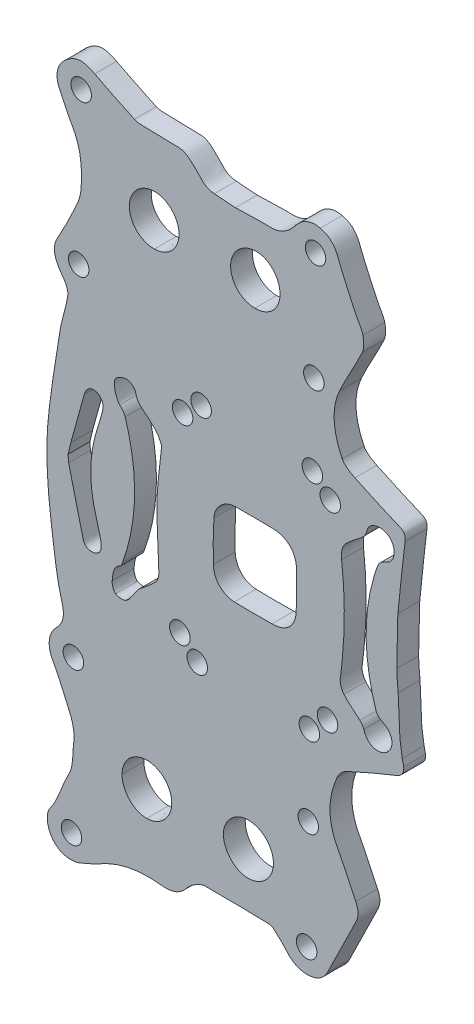
SolidWorks part; units mm, degrees
material "6063-T5"
ref_plane "Front Plane" through (0, 0, 0) normal (0, 0, 1) x (1, 0, 0)
ref_plane "Top Plane" through (0, 0, 0) normal (0, 1, 0) x (1, 0, 0)
ref_plane "Right Plane" through (0, 0, 0) normal (1, 0, 0) x (0, 0, -1)
sketch "Model" plane through (0, 0, 0) normal (0, 0, 1) x (1, 0, 0)
  spline S2 degree 3 poles (131.2621, -129.3744) (131.2709, -130.6129) (131.4296, -131.8502) (131.5219, -133.0884) knots 63 63 63 63 64 64 64 64
  spline S3 degree 3 poles (131.4744, -120.5521) (131.3543, -121.7786) (131.4323, -123.0237) (131.4013, -124.2598) (131.3586, -125.965) (131.2499, -127.67) (131.2621, -129.3744) knots 61 61 61 61 62 62 62 63 63 63 63
  spline S4 degree 3 poles (132.7951, -108.458) (132.2942, -112.482) (131.8696, -116.5161) (131.4744, -120.5521) knots 60 60 60 60 61 61 61 61
  spline S5 degree 3 poles (123.6028, -102.9962) (126.2109, -104.2579) (128.8702, -105.4196) (131.5464, -106.5318) (132.488, -106.9231) (132.9342, -107.3404) (132.7951, -108.458) knots 58 58 58 58 59 59 59 60 60 60 60
  spline S6 degree 3 poles (121.2866, -101.1379) (121.6823, -101.9488) (122.7224, -102.5703) (123.6028, -102.9962) knots 57 57 57 57 58 58 58 58
  spline S7 degree 3 poles (120.8083, -90.5998) (119.1912, -94.1412) (119.6269, -97.7367) (121.2866, -101.1379) knots 56 56 56 56 57 57 57 57
  spline S8 degree 3 poles (124.9527, -82.4768) (123.6758, -85.233) (122.0696, -87.8374) (120.8083, -90.5998) knots 55 55 55 55 56 56 56 56
  spline S9 degree 3 poles (125.0728, -79.6602) (125.2704, -80.5583) (125.3224, -81.6788) (124.9527, -82.4768) knots 54 54 54 54 55 55 55 55
  spline S10 degree 3 poles (117.2743, -66.6092) (119.1395, -67.0215) (120.0739, -68.2761) (120.7134, -70.0591) (121.5761, -72.4641) (122.7552, -74.7568) (123.8228, -77.0865) (124.2216, -77.9567) (124.8735, -78.7549) (125.0728, -79.6602) knots 51 51 51 51 52 52 52 53 53 53 54 54 54 54
  spline S11 degree 3 poles (112.7784, -68.4405) (113.9363, -66.9761) (115.3754, -66.1895) (117.2743, -66.6092) knots 50 50 50 50 51 51 51 51
  spline S12 degree 3 poles (101.7547, -71.1306) (103.8217, -71.1462) (105.895, -70.9292) (107.9557, -71.0251) (110.1482, -71.1272) (111.5494, -69.9949) (112.7784, -68.4405) knots 48 48 48 48 49 49 49 50 50 50 50
  spline S13 degree 3 poles (97.9186, -70.8362) (99.1991, -70.9061) (100.4754, -71.121) (101.7547, -71.1306) knots 47 47 47 47 48 48 48 48
  spline S14 degree 3 poles (83.2811, -66.3614) (83.6961, -66.5573) (84.2073, -66.6059) (84.677, -66.6195) (86.9609, -66.6857) (89.248, -66.6758) (91.529, -66.7897) (92.0912, -66.8178) (92.7248, -67.0979) (93.1684, -67.4566) (94.0425, -68.1633) (94.839, -68.976) (95.6061, -69.8018) (96.2471, -70.4918) (96.9995, -70.7861) (97.9186, -70.8362) knots 42 42 42 42 43 43 43 44 44 44 45 45 45 46 46 46 47 47 47 47
  spline S15 degree 3 poles (76.013, -62.8119) (78.3996, -64.0644) (80.843, -65.2104) (83.2811, -66.3614) knots 41 41 41 41 42 42 42 42
  spline S16 degree 3 poles (70.7914, -63.1847) (72.6239, -61.7236) (73.885, -61.6951) (76.013, -62.8119) knots 40 40 40 40 41 41 41 41
  spline S17 degree 3 poles (71.7709, -72.8051) (70.9519, -71.4444) (70.3799, -69.9373) (69.6448, -68.5232) (68.661, -66.631) (69.0881, -64.5427) (70.7914, -63.1847) knots 38 38 38 38 39 39 39 40 40 40 40
  spline S18 degree 3 poles (70.8737, -89.0688) (71.6065, -87.578) (72.344, -86.0859) (72.9834, -84.5543) (73.2799, -83.844) (73.445, -83.0467) (73.506, -82.276) (73.7672, -78.9734) (73.5511, -75.7629) (71.7709, -72.8051) knots 35 35 35 35 36 36 36 37 37 37 38 38 38 38
  spline S19 degree 3 poles (69.2525, -92.1206) (69.8241, -91.121) (70.3657, -90.1022) (70.8737, -89.0688) knots 34 34 34 34 35 35 35 35
  spline S20 degree 3 poles (70.2491, -97.9212) (68.5299, -95.6807) (68.18, -93.9961) (69.2525, -92.1206) knots 33 33 33 33 34 34 34 34
  spline S21 degree 3 poles (69.6835, -106.5673) (70.0238, -104.4884) (70.7894, -102.4772) (71.098, -100.3962) (71.2131, -99.6199) (70.7621, -98.5898) (70.2491, -97.9212) knots 31 31 31 31 32 32 32 33 33 33 33
  spline S22 degree 3 poles (68.8825, -154.1637) (70.1754, -152.847) (70.6171, -151.5343) (70.0579, -149.6094) (69.2913, -146.9711) (68.9021, -144.2082) (68.5286, -141.4745) (68.0398, -137.8969) (67.5766, -134.3037) (67.3792, -130.702) (67.2105, -127.6229) (67.2049, -124.498) (67.5331, -121.4368) (68.0666, -116.4602) (68.8746, -111.5097) (69.6835, -106.5673) knots 26 26 26 26 27 27 27 28 28 28 29 29 29 30 30 30 31 31 31 31
  spline S23 degree 3 poles (70.0187, -162.98) (69.5139, -161.7064) (68.8376, -160.4987) (68.2088, -159.2766) (67.3417, -157.5917) (67.5553, -155.5153) (68.8825, -154.1637) knots 24 24 24 24 25 25 25 26 26 26 26
  spline S24 degree 3 poles (71.19, -176.2685) (72.226, -174.4286) (71.9124, -172.5334) (72.1785, -170.6477) (72.5911, -167.7229) (70.9986, -165.4523) (70.0187, -162.98) knots 22 22 22 22 23 23 23 24 24 24 24
  spline S25 degree 3 poles (67.9123, -183.0899) (69.472, -181) (69.959, -178.4547) (71.19, -176.2685) knots 21 21 21 21 22 22 22 22
  spline S26 degree 3 poles (68.6543, -188.2457) (67.3597, -186.8952) (66.8499, -184.5135) (67.9123, -183.0899) knots 20 20 20 20 21 21 21 21
  spline S27 degree 3 poles (73.5891, -189.0273) (71.9373, -189.8159) (69.8561, -189.4994) (68.6543, -188.2457) knots 19 19 19 19 20 20 20 20
  spline S28 degree 3 poles (88.0896, -185.2231) (84.09, -184.7603) (80.316, -185.4573) (76.8154, -187.5451) (75.8049, -188.1477) (74.6576, -188.5172) (73.5891, -189.0273) knots 17 17 17 17 18 18 18 19 19 19 19
  spline S29 degree 3 poles (92.7396, -183.5045) (91.5121, -184.9979) (89.97, -185.4407) (88.0896, -185.2231) knots 16 16 16 16 17 17 17 17
  spline S30 degree 3 poles (94.2378, -182.1441) (93.6696, -182.4866) (93.1655, -182.9864) (92.7396, -183.5045) knots 15 15 15 15 16 16 16 16
  spline S31 degree 3 poles (96.2737, -181.3648) (95.5884, -181.3697) (94.8559, -181.7716) (94.2378, -182.1441) knots 14 14 14 14 15 15 15 15
  spline S32 degree 3 poles (108.6393, -181.7772) (108.3803, -181.5507) (107.9058, -181.4983) (107.5278, -181.4913) (103.7766, -181.4217) (100.0247, -181.338) (96.2737, -181.3648) knots 12 12 12 12 13 13 13 14 14 14 14
  spline S33 degree 3 poles (111.2803, -184.3557) (110.5005, -183.4113) (109.5649, -182.5867) (108.6393, -181.7772) knots 11 11 11 11 12 12 12 12
  spline S34 degree 3 poles (118.5733, -183.8781) (117.2729, -186.5553) (113.2935, -186.7934) (111.2803, -184.3557) knots 10 10 10 10 11 11 11 11
  spline S35 degree 3 poles (123.7585, -170.0287) (124.3398, -171.1889) (124.311, -172.2503) (123.7248, -173.4112) (121.972, -176.8822) (120.2724, -180.3802) (118.5733, -183.8781) knots 8 8 8 8 9 9 9 10 10 10 10
  spline S36 degree 3 poles (120.3008, -152.1932) (118.764, -155.847) (118.4435, -159.5128) (120.4242, -163.183) (121.6286, -165.4146) (122.6217, -167.7593) (123.7585, -170.0287) knots 6 6 6 6 7 7 7 8 8 8 8
  spline S37 degree 3 poles (122.0485, -150.2778) (121.3171, -150.6223) (120.6208, -151.4322) (120.3008, -152.1932) knots 5 5 5 5 6 6 6 6
  spline S38 degree 3 poles (132.5342, -144.2923) (132.6298, -145.3707) (132.1556, -145.963) (131.1215, -146.377) (128.0654, -147.6006) (125.0254, -148.8756) (122.0485, -150.2778) knots 3 3 3 3 4 4 4 5 5 5 5
  spline S39 degree 3 poles (132.2733, -143.1378) (132.376, -143.5184) (132.4544, -143.906) (132.5342, -144.2923) knots 2 2 2 2 3 3 3 3
  spline S40 degree 3 poles (131.5219, -133.0884) (131.6206, -135.3633) (131.6866, -137.6403) (131.8325, -139.9122) (131.9018, -140.9923) (132.1285, -142.062) (132.2733, -143.1378) knots 0 0 0 0 1 1 1 2 2 2 2
  spline S41 degree 3 poles (108.4591, -133.6995) (111.1483, -133.7214) (112.8323, -132.0289) (112.8944, -129.3444) (112.9179, -128.3305) (112.9312, -127.3163) (112.9491, -126.3022) knots 8 8 8 8 9 9 9 10 10 10 10
  spline S42 degree 3 poles (101.5233, -133.6823) (103.8345, -133.7314) (106.1482, -133.7477) (108.4591, -133.6995) knots 7 7 7 7 8 8 8 8
  spline S43 degree 3 poles (97.7073, -129.6783) (97.7555, -131.9148) (99.4227, -133.6139) (101.5233, -133.6823) knots 6 6 6 6 7 7 7 7
  spline S44 degree 3 poles (97.8185, -122.2377) (97.6935, -124.7139) (97.6538, -127.1995) (97.7073, -129.6783) knots 5 5 5 5 6 6 6 6
  spline S45 degree 3 poles (101.8267, -118.4915) (99.7591, -118.514) (97.9225, -120.1787) (97.8185, -122.2377) knots 4 4 4 4 5 5 5 5
  spline S46 degree 3 poles (108.595, -118.5337) (106.3399, -118.4771) (104.0825, -118.467) (101.8267, -118.4915) knots 3 3 3 3 4 4 4 4
  spline S47 degree 3 poles (112.948, -123.0029) (112.9307, -120.3078) (111.2975, -118.6015) (108.595, -118.5337) knots 2 2 2 2 3 3 3 3
  spline S48 degree 3 poles (112.9491, -126.3022) (112.9491, -125.2024) (112.955, -124.1026) (112.948, -123.0029) knots 1 1 1 1 2 2 2 2
  spline S50 degree 3 poles (130.6895, -110.4826) (130.4117, -109.3894) (129.4187, -108.624) (128.2619, -108.6102) knots 15 15 15 15 16 16 16 16
  spline S51 degree 3 poles (129.2677, -113.4844) (130.5187, -113.0437) (131.0095, -111.7424) (130.6895, -110.4826) knots 14 14 14 14 15 15 15 15
  spline S52 degree 3 poles (127.5001, -138.0315) (125.0686, -130.5363) (125.0173, -123.0329) (127.5171, -115.5325) (127.8297, -114.5948) (128.1917, -113.8634) (129.2677, -113.4844) knots 12 12 12 12 13 13 13 14 14 14 14
  spline S53 degree 3 poles (128.5184, -139.066) (128.1002, -138.8883) (127.636, -138.4503) (127.5001, -138.0315) knots 11 11 11 11 12 12 12 12
  spline S54 degree 3 poles (130.3703, -141.8834) (130.5328, -140.6901) (129.7401, -139.585) (128.5184, -139.066) knots 10 10 10 10 11 11 11 11
  spline S55 degree 3 poles (125.2306, -142.0082) (125.6014, -143.341) (126.6355, -144.2132) (127.9043, -144.1524) (129.1642, -144.0919) (130.1993, -143.1396) (130.3703, -141.8834) knots 8 8 8 8 9 9 9 10 10 10 10
  spline S56 degree 3 poles (124.5298, -140.9482) (124.8337, -141.2314) (125.1219, -141.6173) (125.2306, -142.0082) knots 7 7 7 7 8 8 8 8
  spline S57 degree 3 poles (121.5949, -138.2897) (122.4505, -139.2811) (123.5628, -140.0471) (124.5298, -140.9482) knots 6 6 6 6 7 7 7 7
  spline S58 degree 3 poles (121.1802, -117.2013) (121.9419, -123.5314) (121.7704, -129.8533) (120.9326, -136.1721) (120.8426, -136.8502) (121.1446, -137.768) (121.5949, -138.2897) knots 4 4 4 4 5 5 5 6 6 6 6
  spline S59 degree 3 poles (122.4475, -113.7681) (121.3149, -114.6565) (121.0085, -115.7746) (121.1802, -117.2013) knots 3 3 3 3 4 4 4 4
  spline S60 degree 3 poles (124.0097, -112.4745) (123.4668, -112.8756) (122.9793, -113.3509) (122.4475, -113.7681) knots 2 2 2 2 3 3 3 3
  spline S61 degree 3 poles (128.2619, -108.6102) (127.0917, -108.6072) (126.0871, -109.1446) (125.8387, -110.2192) (125.5725, -111.3709) (124.8162, -111.8786) (124.0097, -112.4745) knots 0 0 0 0 1 1 1 2 2 2 2
  spline S62 degree 3 poles (87.3863, -124.8571) (87.4999, -121.7611) (87.9619, -118.6778) (88.2695, -115.5889) knots 18 18 18 18 19 19 19 19
  spline S63 degree 3 poles (87.1536, -137.7252) (87.5548, -137.3053) (87.7596, -136.5217) (87.7457, -135.9103) (87.6624, -132.2247) (87.3628, -128.5403) (87.3863, -124.8571) knots 16 16 16 16 17 17 17 18 18 18 18
  spline S64 degree 3 poles (84.0384, -140.4346) (85.0644, -139.5158) (86.2072, -138.7156) (87.1536, -137.7252) knots 15 15 15 15 16 16 16 16
  spline S65 degree 3 poles (81.746, -143.333) (82.4006, -142.9395) (82.8033, -142.1205) (83.2995, -141.4728) (83.5583, -141.1351) (83.7299, -140.7108) (84.0384, -140.4346) knots 13 13 13 13 14 14 14 15 15 15 15
  spline S66 degree 3 poles (79.8323, -143.238) (80.2984, -143.5583) (81.2705, -143.6188) (81.746, -143.333) knots 12 12 12 12 13 13 13 13
  spline S67 degree 3 poles (79.2135, -141.498) (79.1586, -142.0768) (79.4106, -142.9481) (79.8323, -143.238) knots 11 11 11 11 12 12 12 12
  spline S68 degree 3 poles (81.1409, -137.576) (81.0375, -137.8639) (80.9299, -138.2624) (80.7058, -138.3765) (79.3938, -139.0441) (79.3247, -140.3253) (79.2135, -141.498) knots 9 9 9 9 10 10 10 11 11 11 11
  spline S69 degree 3 poles (81.5862, -114.3349) (84.0003, -122.1253) (83.9046, -129.8801) (81.1409, -137.576) knots 8 8 8 8 9 9 9 9
  spline S70 degree 3 poles (80.5985, -112.95) (81.0059, -113.3344) (81.4259, -113.8176) (81.5862, -114.3349) knots 7 7 7 7 8 8 8 8
  spline S71 degree 3 poles (79.869, -109.1158) (79.2514, -109.8269) (79.8784, -112.2706) (80.5985, -112.95) knots 6 6 6 6 7 7 7 7
  spline S72 degree 3 poles (81.6581, -108.2611) (81.0303, -108.3141) (80.2734, -108.6502) (79.869, -109.1158) knots 5 5 5 5 6 6 6 6
  spline S73 degree 3 poles (83.544, -109.6716) (83.364, -108.8037) (82.5746, -108.1837) (81.6581, -108.2611) knots 4 4 4 4 5 5 5 5
  spline S74 degree 3 poles (85.3689, -112.0434) (84.5452, -111.3996) (83.783, -110.8244) (83.544, -109.6716) knots 3 3 3 3 4 4 4 4
  spline S75 degree 3 poles (88.2695, -115.5889) (88.0038, -115.0585) (87.8281, -114.4505) (87.4522, -114.0154) (86.8294, -113.2946) (86.1203, -112.6307) (85.3689, -112.0434) knots 1 1 1 1 2 2 2 3 3 3 3
  spline S77 degree 3 poles (71.6441, -123.4022) (71.4298, -124.1849) (71.2714, -124.983) (71.1544, -125.4853) knots 11 11 11 11 12 12 12 12
  spline S78 degree 3 poles (74.1067, -114.525) (73.2832, -117.4833) (72.455, -120.4404) (71.6441, -123.4022) knots 10 10 10 10 11 11 11 11
  spline S79 degree 3 poles (76.3309, -133.064) (74.8946, -128.282) (74.94, -123.5239) (76.4924, -118.7747) (76.8598, -117.6508) (77.1968, -116.5135) (77.4734, -115.3644) (77.746, -114.2318) (77.1862, -113.2318) (76.2454, -113.0001) (75.2542, -112.756) (74.4378, -113.3357) (74.1067, -114.525) knots 6 6 6 6 7 7 7 8 8 8 9 9 9 10 10 10 10
  spline S80 degree 3 poles (77.0862, -135.9234) (76.8606, -134.964) (76.6144, -134.0078) (76.3309, -133.064) knots 5 5 5 5 6 6 6 6
  spline S81 degree 3 poles (77.2094, -137.1756) (77.2392, -136.7624) (77.1817, -136.3293) (77.0862, -135.9234) knots 4 4 4 4 5 5 5 5
  spline S82 degree 3 poles (71.2525, -126.8093) (72.126, -130.3946) (72.9987, -133.9804) (73.9131, -137.5554) (74.1366, -138.429) (74.806, -138.8549) (75.7127, -138.7396) (76.6035, -138.6262) (77.1437, -138.0837) (77.2094, -137.1756) knots 1 1 1 1 2 2 2 3 3 3 4 4 4 4
  spline S83 degree 3 poles (71.1544, -125.4853) (71.199, -126.1367) (71.1736, -126.4857) (71.2525, -126.8093) knots 0 0 0 0 1 1 1 1
  spline S84 degree 3 poles (104.0828, -166.9391) (101.7241, -166.9346) (99.5525, -169.073) (99.5441, -171.4082) (99.5351, -173.9038) (101.6158, -176.1491) (103.973, -176.1875) (106.5405, -176.2293) (108.6831, -174.1375) (108.7079, -171.5647) knots 1 1 1 1 2 2 2 3 3 3 4 4 4 4
  spline S85 degree 3 poles (108.7079, -171.5647) (108.7323, -169.0338) (106.6427, -166.9439) (104.0828, -166.9391) knots 0 0 0 0 1 1 1 1
  spline S86 degree 3 poles (85.5248, -175.9802) (87.9639, -175.9662) (90.0848, -173.8209) (90.1105, -171.3418) knots 3 3 3 3 4 4 4 4
  spline S87 degree 3 poles (81.0181, -171.2104) (80.9855, -173.7629) (83.0938, -175.9942) (85.5248, -175.9802) knots 2 2 2 2 3 3 3 3
  spline S88 degree 3 poles (85.578, -166.7462) (83.0611, -166.7291) (81.0502, -168.6978) (81.0181, -171.2104) knots 1 1 1 1 2 2 2 2
  spline S89 degree 3 poles (90.1105, -171.3418) (90.1368, -168.8104) (88.1179, -166.7635) (85.578, -166.7462) knots 0 0 0 0 1 1 1 1
  spline S90 degree 3 poles (86.9384, -75.9576) (84.3914, -75.9918) (82.3319, -78.0969) (82.3546, -80.6428) (82.3769, -83.1416) (84.4029, -85.1084) (86.9383, -85.0924) knots 2 2 2 2 3 3 3 4 4 4 4
  spline S91 degree 3 poles (91.44, -80.5223) (91.4516, -78.0428) (89.3632, -75.925) (86.9384, -75.9576) knots 1 1 1 1 2 2 2 2
  spline S92 degree 3 poles (86.9383, -85.0924) (89.4029, -85.0769) (91.4283, -83.0208) (91.44, -80.5223) knots 0 0 0 0 1 1 1 1
  spline S93 degree 3 poles (109.9163, -80.7971) (109.9394, -78.2916) (107.9674, -76.1541) (105.6215, -76.1418) (103.0489, -76.1282) (100.9021, -78.2289) (100.8777, -80.784) (100.8539, -83.2584) (102.8103, -85.2412) (105.3046, -85.2708) knots 1 1 1 1 2 2 2 3 3 3 4 4 4 4
  spline S94 degree 3 poles (105.3046, -85.2708) (107.8883, -85.3015) (109.8927, -83.3571) (109.9163, -80.7971) knots 0 0 0 0 1 1 1 1
  spline S95 degree 3 poles (69.9219, -185.0443) (69.8758, -186.0285) (70.6837, -186.8396) (71.7372, -186.8668) knots 3 3 3 3 4 4 4 4
  spline S96 degree 3 poles (71.8055, -183.3786) (70.8187, -183.3419) (69.9664, -184.0957) (69.9219, -185.0443) knots 2 2 2 2 3 3 3 3
  spline S97 degree 3 poles (71.7372, -186.8668) (72.652, -186.8904) (73.4439, -186.1147) (73.4781, -185.1616) (73.5109, -184.2467) (72.7287, -183.4129) (71.8055, -183.3786) knots 0 0 0 0 1 1 1 2 2 2 2
  spline S98 degree 3 poles (114.8563, -183.4784) (115.7659, -183.4757) (116.5169, -182.6852) (116.536, -181.7104) knots 3 3 3 3 4 4 4 4
  spline S99 degree 3 poles (113.0323, -181.6426) (113.0173, -182.6287) (113.8644, -183.4813) (114.8563, -183.4784) knots 2 2 2 2 3 3 3 3
  spline S100 degree 3 poles (114.8715, -179.9573) (113.8711, -179.9251) (113.047, -180.6803) (113.0323, -181.6426) knots 1 1 1 1 2 2 2 2
  spline S101 degree 3 poles (116.536, -181.7104) (116.555, -180.7421) (115.8394, -179.9884) (114.8715, -179.9573) knots 0 0 0 0 1 1 1 1
  spline S102 degree 3 poles (116.8353, -161.6866) (116.8139, -160.7501) (116.027, -159.986) (115.0953, -159.9971) (114.0697, -160.0094) (113.3208, -160.7497) (113.3321, -161.74) knots 2 2 2 2 3 3 3 4 4 4 4
  spline S103 degree 3 poles (113.3321, -161.74) (113.3433, -162.7248) (114.1141, -163.4784) (115.1123, -163.4805) (116.0761, -163.4826) (116.8576, -162.6689) (116.8353, -161.6866) knots 0 0 0 0 1 1 1 2 2 2 2
  spline S104 degree 3 poles (70.3257, -157.1435) (70.3075, -158.1326) (71.0621, -158.8752) (72.0954, -158.8849) knots 3 3 3 3 4 4 4 4
  spline S105 degree 3 poles (72.1433, -155.4366) (71.1203, -155.419) (70.344, -156.148) (70.3257, -157.1435) knots 2 2 2 2 3 3 3 3
  spline S106 degree 3 poles (73.8241, -157.1846) (73.8525, -156.2368) (73.0988, -155.4531) (72.1433, -155.4366) knots 1 1 1 1 2 2 2 2
  spline S107 degree 3 poles (72.0954, -158.8849) (73.0645, -158.8941) (73.7944, -158.1761) (73.8241, -157.1846) knots 0 0 0 0 1 1 1 1
  spline S108 degree 3 poles (118.1665, -70.9051) (118.1749, -70.0051) (117.4628, -69.3102) (116.5381, -69.316) knots 3 3 3 3 4 4 4 4
  spline S109 degree 3 poles (116.4055, -72.6323) (117.3426, -72.6035) (118.1581, -71.8038) (118.1665, -70.9051) knots 2 2 2 2 3 3 3 3
  spline S110 degree 3 poles (116.5381, -69.316) (115.4635, -69.3227) (114.6285, -70.0387) (114.6262, -70.9555) (114.6239, -71.8595) (115.4742, -72.6608) (116.4055, -72.6323) knots 0 0 0 0 1 1 1 2 2 2 2
  spline S111 degree 3 poles (73.2231, -92.7879) (72.0923, -92.7896) (71.324, -93.4391) (71.3324, -94.3863) knots 3 3 3 3 4 4 4 4
  spline S112 degree 3 poles (74.8301, -94.2868) (74.8069, -93.4508) (74.0947, -92.7866) (73.2231, -92.7879) knots 2 2 2 2 3 3 3 3
  spline S113 degree 3 poles (73.0827, -96.0577) (74.0642, -96.0654) (74.8572, -95.2616) (74.8301, -94.2868) knots 1 1 1 1 2 2 2 2
  spline S114 degree 3 poles (71.3324, -94.3863) (71.3408, -95.3293) (72.0954, -96.05) (73.0827, -96.0577) knots 0 0 0 0 1 1 1 1
  spline S115 degree 3 poles (93.0712, -146.5723) (93.0389, -147.5627) (93.8081, -148.351) (94.8063, -148.3506) (95.7069, -148.3502) (96.463, -147.5988) (96.4838, -146.6836) knots 2 2 2 2 3 3 3 4 4 4 4
  spline S116 degree 3 poles (94.876, -144.9608) (93.8811, -144.9319) (93.102, -145.6276) (93.0712, -146.5723) knots 1 1 1 1 2 2 2 2
  spline S117 degree 3 poles (96.4838, -146.6836) (96.5048, -145.7594) (95.7841, -144.9872) (94.876, -144.9608) knots 0 0 0 0 1 1 1 1
  spline S118 degree 3 poles (117.0023, -146.9544) (117.0178, -146.0135) (116.3084, -145.2689) (115.3807, -145.2524) (114.3285, -145.2337) (113.5316, -145.9681) (113.5534, -146.9362) (113.5746, -147.8794) (114.3495, -148.6092) (115.3266, -148.6062) knots 1 1 1 1 2 2 2 3 3 3 4 4 4 4
  spline S119 degree 3 poles (115.3266, -148.6062) (116.2681, -148.6033) (116.9868, -147.8948) (117.0023, -146.9544) knots 0 0 0 0 1 1 1 1
  spline S120 degree 3 poles (114.3747, -90.9568) (114.391, -91.8885) (115.0915, -92.5293) (116.0956, -92.5311) knots 3 3 3 3 4 4 4 4
  spline S121 degree 3 poles (116.0956, -92.5311) (117.0735, -92.5328) (117.842, -91.7957) (117.8451, -90.853) (117.848, -89.9813) (117.2222, -89.3202) (116.3908, -89.3166) (115.0926, -89.3109) (114.3564, -89.9099) (114.3747, -90.9568) knots 0 0 0 0 1 1 1 2 2 2 3 3 3 3
  spline S122 degree 3 poles (71.7202, -66.4559) (71.7129, -67.4203) (72.506, -68.1574) (73.5395, -68.1467) knots 3 3 3 3 4 4 4 4
  spline S123 degree 3 poles (73.5395, -68.1467) (74.5048, -68.1368) (75.2187, -67.3948) (75.2105, -66.4101) (75.2032, -65.531) (74.6261, -64.8965) (73.8488, -64.913) (72.5046, -64.9416) (71.7273, -65.505) (71.7202, -66.4559) knots 0 0 0 0 1 1 1 2 2 2 3 3 3 3
  spline S124 degree 3 poles (89.8591, -143.5403) (89.8708, -144.4851) (90.6386, -145.1824) (91.6516, -145.1683) (92.5793, -145.1553) (93.3018, -144.4128) (93.2935, -143.4808) (93.2853, -142.5416) (92.5696, -141.865) (91.5969, -141.8766) knots 1 1 1 1 2 2 2 3 3 3 4 4 4 4
  spline S125 degree 3 poles (91.5969, -141.8766) (90.5573, -141.8891) (89.8471, -142.569) (89.8591, -143.5403) knots 0 0 0 0 1 1 1 1
  spline S126 degree 3 poles (119.1542, -107.1357) (118.1244, -107.1587) (117.3905, -107.8456) (117.3809, -108.7956) (117.3718, -109.6958) (118.1452, -110.4192) (119.1007, -110.404) knots 2 2 2 2 3 3 3 4 4 4 4
  spline S127 degree 3 poles (120.7621, -108.7299) (120.7594, -107.8024) (120.0665, -107.1154) (119.1542, -107.1357) knots 1 1 1 1 2 2 2 2
  spline S128 degree 3 poles (119.1007, -110.404) (120.0404, -110.3891) (120.7648, -109.6592) (120.7621, -108.7299) knots 0 0 0 0 1 1 1 1
  spline S129 degree 3 poles (116.9173, -143.8473) (116.9177, -144.8173) (117.6499, -145.5225) (118.6542, -145.5201) (119.6297, -145.5177) (120.2767, -144.8588) (120.2818, -143.8624) knots 2 2 2 2 3 3 3 4 4 4 4
  spline S130 degree 3 poles (120.2818, -143.8624) (120.2869, -142.8525) (119.66, -142.2079) (118.6683, -142.2034) (117.6299, -142.1986) (116.917, -142.868) (116.9173, -143.8473) knots 0 0 0 0 1 1 1 2 2 2 2
  spline S131 degree 3 poles (115.8241, -107.4013) (116.7441, -107.4236) (117.4956, -106.6956) (117.5175, -105.7609) (117.5393, -104.8284) (116.9399, -104.1994) (116.0177, -104.1871) knots 2 2 2 2 3 3 3 4 4 4 4
  spline S132 degree 3 poles (114.1026, -105.6711) (114.0743, -106.5933) (114.8549, -107.3779) (115.8241, -107.4013) knots 1 1 1 1 2 2 2 2
  spline S133 degree 3 poles (116.0177, -104.1871) (114.9014, -104.1722) (114.1303, -104.7698) (114.1026, -105.6711) knots 0 0 0 0 1 1 1 1
  spline S134 degree 3 poles (93.8069, -108.4292) (93.8194, -107.5299) (93.2495, -106.9148) (92.3773, -106.8861) knots 3 3 3 3 4 4 4 4
  spline S135 degree 3 poles (92.3773, -106.8861) (91.2331, -106.8485) (90.4168, -107.4555) (90.3816, -108.3702) (90.3474, -109.2549) (91.0909, -110.0182) (92.0293, -110.062) (93.0008, -110.1074) (93.7937, -109.379) (93.8069, -108.4292) knots 0 0 0 0 1 1 1 2 2 2 3 3 3 3
  spline S136 degree 3 poles (95.4823, -107.1631) (96.342, -107.1404) (97.0366, -106.3916) (97.0441, -105.4795) (97.0517, -104.5609) (96.4708, -103.9498) (95.5997, -103.9599) knots 2 2 2 2 3 3 3 4 4 4 4
  spline S137 degree 3 poles (95.5997, -103.9599) (94.4706, -103.9731) (93.668, -104.5858) (93.6609, -105.44) (93.6529, -106.4041) (94.4832, -107.1895) (95.4823, -107.1631) knots 0 0 0 0 1 1 1 2 2 2 2
extrude "Boss-Extrude4" add sketch "Model" along normal blind 4
sketch "Sketch1" plane through (0, 0, 4) normal (0, 0, 1) x (1, 0, 0)
  line L0 (95.4823, -107.1631) -> (95.4823, -103.9635)
  line L1 (93.8069, -108.4292) -> (90.3804, -108.4292)
  line L2 (115.8241, -107.4013) -> (115.8241, -104.1908)
  line L3 (119.1007, -110.404) -> (119.1007, -107.1375)
  line L4 (116.0956, -92.5311) -> (116.0956, -89.3264)
  line L5 (116.4055, -72.6323) -> (116.4055, -69.3204)
  line L6 (73.5395, -68.1467) -> (73.5395, -64.9299)
  line L7 (73.0827, -96.0577) -> (73.0827, -92.7915)
  line L8 (116.9173, -143.8473) -> (120.2818, -143.8624)
  line L9 (117.0023, -146.9544) -> (113.5539, -146.9544)
  line L10 (96.4838, -146.6836) -> (93.0712, -146.5723)
  line L11 (91.5969, -141.8766) -> (91.5969, -145.1683)
  line L12 (72.1433, -155.4366) -> (72.0954, -158.8849)
  line L13 (72.0954, -158.8849) -> (71.8055, -183.3786)
  line L14 (71.8055, -183.3786) -> (71.7372, -186.8668)
  line L15 (116.8353, -161.6866) -> (113.3321, -161.74)
  line L16 (116.536, -181.7104) -> (113.0323, -181.6426)
  circle A0 centre (73.0827, -94.4246) radius 1.875
  circle A1 centre (73.5395, -66.5383) radius 1.875
  circle A2 centre (95.4823, -105.5633) radius 1.875
  circle A3 centre (92.0937, -108.4292) radius 1.875
  circle A4 centre (115.8241, -105.796) radius 1.875
  circle A5 centre (119.1007, -108.7708) radius 1.875
  circle A6 centre (116.0956, -90.9287) radius 1.875
  circle A7 centre (116.4055, -70.9764) radius 1.875
  circle A8 centre (118.5996, -143.8549) radius 1.875
  circle A9 centre (115.2781, -146.9544) radius 1.875
  circle A10 centre (115.0837, -161.7133) radius 1.875
  circle A11 centre (114.7842, -181.6765) radius 1.875
  circle A12 centre (94.7775, -146.628) radius 1.875
  circle A13 centre (91.5969, -143.5225) radius 1.875
  circle A14 centre (72.1194, -157.1608) radius 1.875
  circle A15 centre (71.7714, -185.1227) radius 1.875
  spline S0 degree 3 poles (95.5997, -103.9599) (94.4706, -103.9731) (93.668, -104.5858) (93.6609, -105.44) (93.6529, -106.4041) (94.4832, -107.1895) (95.4823, -107.1631) knots 0 0 0 0 1 1 1 2 2 2 2 construction
  spline S1 degree 3 poles (92.3773, -106.8861) (91.2331, -106.8485) (90.4168, -107.4555) (90.3816, -108.3702) (90.3474, -109.2549) (91.0909, -110.0182) (92.0293, -110.062) (93.0008, -110.1074) (93.7937, -109.379) (93.8069, -108.4292) knots 0 0 0 0 1 1 1 2 2 2 3 3 3 3 construction
  spline S2 degree 3 poles (116.0177, -104.1871) (114.9014, -104.1722) (114.1303, -104.7698) (114.1026, -105.6711) knots 0 0 0 0 1 1 1 1 construction
  spline S3 degree 3 poles (119.1542, -107.1357) (118.1244, -107.1587) (117.3905, -107.8456) (117.3809, -108.7956) (117.3718, -109.6958) (118.1452, -110.4192) (119.1007, -110.404) knots 2 2 2 2 3 3 3 4 4 4 4 construction
  spline S4 degree 3 poles (116.0956, -92.5311) (117.0735, -92.5328) (117.842, -91.7957) (117.8451, -90.853) (117.848, -89.9813) (117.2222, -89.3202) (116.3908, -89.3166) (115.0926, -89.3109) (114.3564, -89.9099) (114.3747, -90.9568) knots 0 0 0 0 1 1 1 2 2 2 3 3 3 3 construction
  spline S5 degree 3 poles (116.5381, -69.316) (115.4635, -69.3227) (114.6285, -70.0387) (114.6262, -70.9555) (114.6239, -71.8595) (115.4742, -72.6608) (116.4055, -72.6323) knots 0 0 0 0 1 1 1 2 2 2 2 construction
  spline S6 degree 3 poles (73.5395, -68.1467) (74.5048, -68.1368) (75.2187, -67.3948) (75.2105, -66.4101) (75.2032, -65.531) (74.6261, -64.8965) (73.8488, -64.913) (72.5046, -64.9416) (71.7273, -65.505) (71.7202, -66.4559) knots 0 0 0 0 1 1 1 2 2 2 3 3 3 3 construction
  spline S7 degree 3 poles (73.2231, -92.7879) (72.0923, -92.7896) (71.324, -93.4391) (71.3324, -94.3863) knots 3 3 3 3 4 4 4 4 construction
  spline S8 degree 3 poles (117.0023, -146.9544) (117.0178, -146.0135) (116.3084, -145.2689) (115.3807, -145.2524) (114.3285, -145.2337) (113.5316, -145.9681) (113.5534, -146.9362) (113.5746, -147.8794) (114.3495, -148.6092) (115.3266, -148.6062) knots 1 1 1 1 2 2 2 3 3 3 4 4 4 4 construction
  spline S9 degree 3 poles (89.8591, -143.5403) (89.8708, -144.4851) (90.6386, -145.1824) (91.6516, -145.1683) (92.5793, -145.1553) (93.3018, -144.4128) (93.2935, -143.4808) (93.2853, -142.5416) (92.5696, -141.865) (91.5969, -141.8766) knots 1 1 1 1 2 2 2 3 3 3 4 4 4 4 construction
  spline S10 degree 3 poles (113.3321, -161.74) (113.3433, -162.7248) (114.1141, -163.4784) (115.1123, -163.4805) (116.0761, -163.4826) (116.8576, -162.6689) (116.8353, -161.6866) knots 0 0 0 0 1 1 1 2 2 2 2 construction
  spline S11 degree 3 poles (116.8353, -161.6866) (116.8139, -160.7501) (116.027, -159.986) (115.0953, -159.9971) (114.0697, -160.0094) (113.3208, -160.7497) (113.3321, -161.74) knots 2 2 2 2 3 3 3 4 4 4 4 construction
  dimension "D1" = 3.75
  dimension "D2" = 3.75
  dimension "D3" = 3.75
  dimension "D4" = 3.75
  dimension "D5" = 3.75
  dimension "D6" = 3.75
  dimension "D7" = 3.75
  dimension "D8" = 3.75
  dimension "D9" = 3.75
  dimension "D10" = 3.75
  dimension "D11" = 3.75
  dimension "D12" = 3.75
  dimension "D13" = 3.75
  dimension "D14" = 3.75
  dimension "D15" = 3.75
  dimension "D16" = 3.75
extrude "Cut-Extrude1" cut sketch "Sketch1" against normal through all contours A1 | A0 | A3 | A2 | A5 | A4 | A6 | A7 | A8 | A9 | A10 | A11 | A12 | A13 | A14 | A15
ref_plane "Plane1" through (105.0681, -118.4814, 4) normal (-0.005, -1, 0) x (-1, 0.005, 0)
ref_plane "Plane2" through (105.0299, -126.0663, 4) normal (-0.005, -1, 0) x (-1, 0.005, 0)
